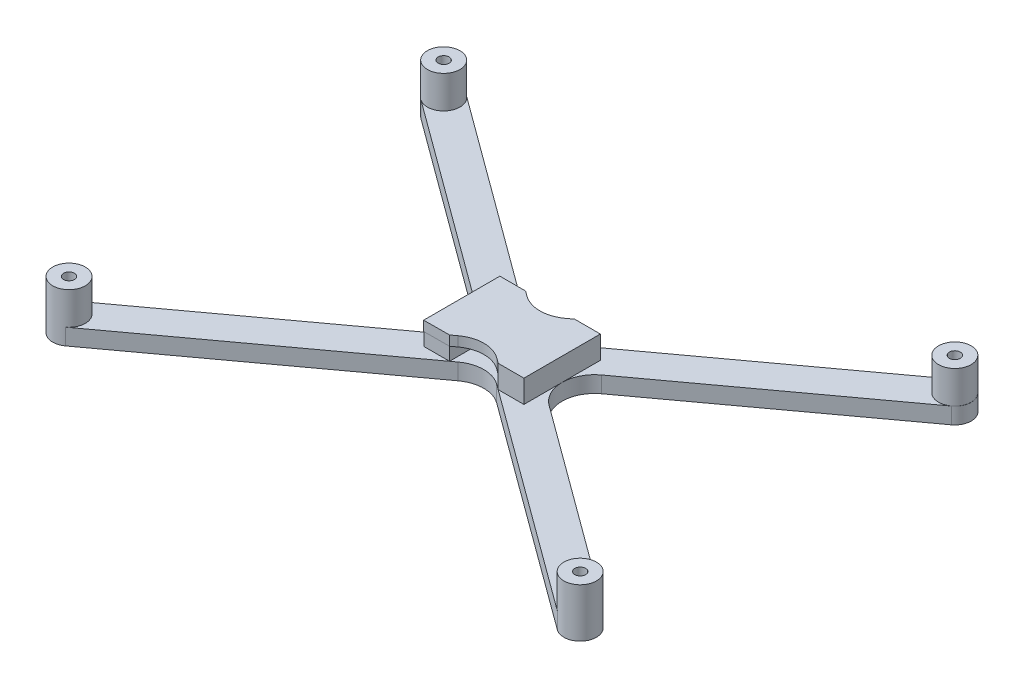
SolidWorks part; units mm, degrees
ref_plane "Front Plane" through (0, 0, 0) normal (0, 0, 1) x (1, 0, 0)
ref_plane "Top Plane" through (0, 0, 0) normal (0, 1, 0) x (1, 0, 0)
ref_plane "Right Plane" through (0, 0, 0) normal (1, 0, 0) x (0, 0, -1)
sketch "Sketch1" plane through (0, 0, 0) normal (0, 1, 0) x (1, 0, 0)
  line L13 (78.45, 57.5) -> (-78.45, 57.5)
  line L14 (78.45, 57.5) -> (78.45, -57.5)
  line L15 (78.45, -57.5) -> (-78.45, -57.5)
  line L16 (-78.45, 57.5) -> (-78.45, -57.5)
  dimension "D1" = 57.5
  dimension "D2" = 115
  dimension "D3" = 78.45
  dimension "D4" = 156.9
sketch "Sketch2" plane through (0, 0, 0) normal (0, 1, 0) x (1, 0, 0)
  line L0 (-85.4386, 56.4231) -> (-19.4732, 8.0737)
  line L1 (-85.4386, 56.4231) -> (-79.5269, 64.4886)
  line L2 (79.5278, -64.4874) -> (85.4386, -56.4231)
  line L3 (19.5014, -8.0944) -> (85.4386, -56.4231)
  line L4 (19.5001, 8.0357) -> (85.4854, 56.4171)
  line L5 (-79.5257, -64.4888) -> (-85.4388, -56.4243)
  line L6 (85.4854, 56.4171) -> (79.5329, 64.5354)
  line L7 (-85.4388, -56.4243) -> (-19.4718, -8.0563)
  line L8 (-5.9462, -10.5392) -> (-79.5257, -64.4888)
  line L9 (79.5278, -64.4874) -> (5.8761, -10.5365)
  line L10 (-79.5269, 64.4886) -> (-5.9273, 10.5437)
  line L11 (5.8973, 10.5447) -> (79.5329, 64.5354)
  circle A0 centre (-78.45, 57.5) radius 1.675
  circle A1 centre (-78.45, -57.5) radius 1.675
  circle A2 centre (78.45, -57.5) radius 1.675
  circle A3 centre (78.45, 57.5) radius 1.675
  circle A4 centre (-78.45, 57.5) radius 5
  circle A5 centre (78.45, 57.5) radius 5.0334
  circle A6 centre (78.45, -57.5) radius 5
  circle A7 centre (-78.45, -57.5) radius 5
  arc A8 (-19.4718, -8.0563) -> (-19.4732, 8.0737) centre (-25.3849, 0.0082) ccw
  arc A9 (19.5001, 8.0357) -> (19.5014, -8.0944) centre (25.4131, -0.0289) ccw
  arc A10 (5.8973, 10.5447) -> (-5.9273, 10.5437) centre (-0.0157, 18.6092) cw
  arc A11 (-5.9462, -10.5392) -> (5.8761, -10.5365) centre (-0.0332, -18.6037) cw
  dimension "D1" = 3.35
  dimension "D5" = 5
  dimension "D6" = 5
  dimension "D8" = 5
  dimension "D9" = 5
  dimension "D12" = 10
  dimension "D13" = 10
  dimension "D14" = 10
  dimension "D15" = 10
  dimension "D3" = 5
extrude "Boss-Extrude2" add sketch "Sketch2" along normal blind 5 contours A7 A1 | A4 A0 | A5 A3 | A6 A2 | L8 A11 L9 L2 A6 L3 A9 L4 A5 L11 A10 L10 A4 L0 A8 L7 A7 L5
sketch "Sketch4" plane through (0, 5, 0) normal (0, 1, 0) x (1, 0, 0)
  circle A0 centre (-78.45, 57.5) radius 5
  circle A1 centre (78.45, 57.5) radius 5
  circle A2 centre (-78.45, -57.5) radius 5
  circle A3 centre (78.45, -57.5) radius 5
  circle A4 centre (-78.45, 57.5) radius 1.675
  circle A5 centre (78.45, 57.5) radius 1.675
  circle A6 centre (78.45, -57.5) radius 1.675
  circle A7 centre (-78.45, -57.5) radius 1.675
  point P17 (0, 0)
extrude "Boss-Extrude3" add sketch "Sketch4" along normal blind 10
sketch "Sketch7" plane through (0, 5, 0) normal (0, 1, 0) x (1, 0, 0)
  line L0 (-5.9462, -10.5392) -> (-75.4935, -61.5323) construction
  line L2 (-15.3849, 0.009) -> (-15.3849, -11.6681)
  line L3 (-15.3849, -11.6681) -> (-7.4859, -11.6681)
  line L4 (-7.4859, -0.1373) -> (-7.4859, -11.6681)
  line L5 (-75.4942, 61.5328) -> (-5.9273, 10.5437) construction
  line L7 (-15.3849, 0.009) -> (-15.3849, 11.686)
  line L8 (-15.3849, 11.686) -> (-7.4859, 11.686)
  line L9 (-7.4859, -0.1373) -> (-7.4859, 11.686)
  line L10 (75.4953, -61.5336) -> (5.8761, -10.5365) construction
  line L11 (7.5141, -11.7363) -> (15.4131, -11.7363)
  line L12 (7.5141, -11.7363) -> (7.5141, 11.7302)
  line L13 (7.5141, 11.7302) -> (15.4131, 11.7302)
  line L14 (15.4131, -11.7363) -> (15.4131, 11.7302)
  line L15 (5.8973, 10.5447) -> (75.4738, 61.5592) construction
  arc A0 (-19.4718, -8.0563) -> (-19.4732, 8.0737) centre (-25.3849, 0.0082) ccw construction
  arc A1 (19.5001, 8.0357) -> (19.5014, -8.0944) centre (25.4131, -0.0289) ccw construction
  dimension "D1" = 15
extrude "Boss-Extrude4" add sketch "Sketch7" along normal blind 4
sketch "Sketch8" plane through (0, 9, 0) normal (0, 1, 0) x (1, 0, 0)
  line L0 (-15.3849, -11.7229) -> (-7.4859, -11.6681)
  line L2 (-15.3849, 11.686) -> (-15.3849, -11.7229)
  line L4 (15.4131, 11.7302) -> (15.4131, -11.7363)
  line L5 (15.4131, -11.7363) -> (7.5141, -11.7363)
  line L8 (-15.3849, 11.686) -> (-7.4859, 11.686)
  line L9 (15.4131, 11.7302) -> (7.5141, 11.7302)
  line L10 (-7.4859, 11.686) -> (-5.9286, 10.542)
  line L11 (5.949, 10.5693) -> (7.5141, 11.7302)
  line L12 (-7.4859, -11.6681) -> (-5.9435, -10.535)
  line L13 (5.9416, -10.5678) -> (7.5141, -11.7363)
  arc A1 (5.949, 10.5693) -> (-5.9286, 10.542) centre (-0.0083, 18.6012) cw
  arc A2 (-5.9435, -10.535) -> (5.9416, -10.5678) centre (-0.0231, -18.5941) cw
  dimension "D1" = 10
  dimension "D2" = 10
extrude "Boss-Extrude5" add sketch "Sketch8" along normal blind 3
equation "\"D1@Sketch1\"=\"D2@Sketch1\"/2"
equation "\"D3@Sketch1\"=\"D4@Sketch1\"/2"
